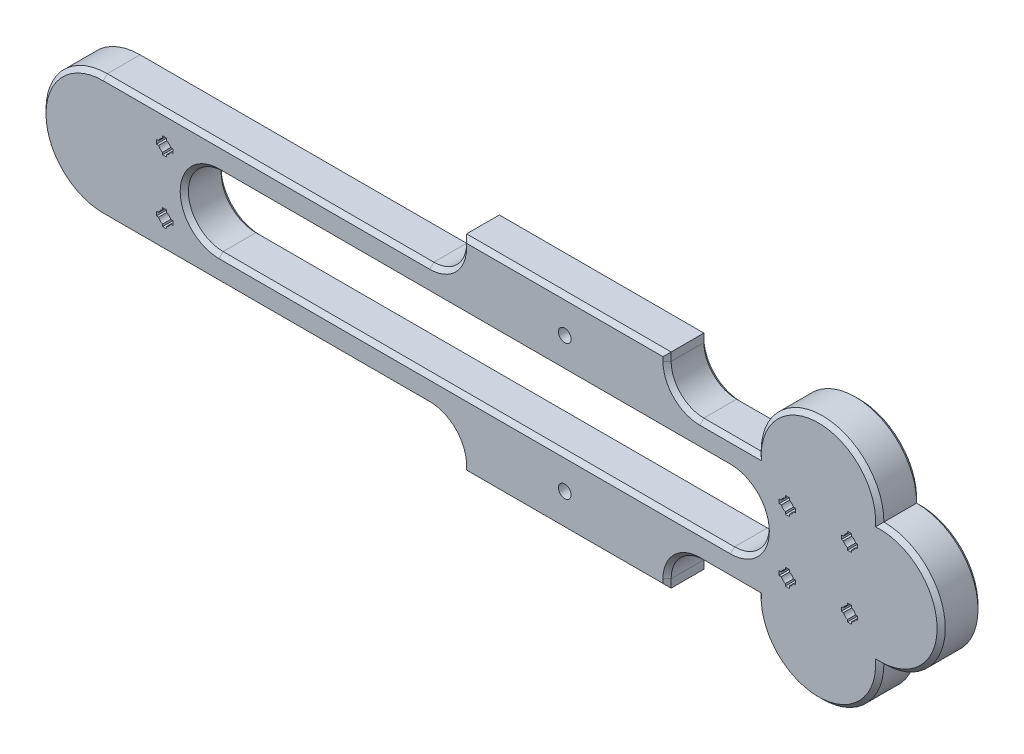
SolidWorks part; units mm, degrees
ref_plane "Front Plane" through (0, 0, 0) normal (0, 0, 1) x (1, 0, 0)
ref_plane "Top Plane" through (0, 0, 0) normal (0, 1, 0) x (1, 0, 0)
ref_plane "Right Plane" through (0, 0, 0) normal (1, 0, 0) x (0, 0, -1)
sketch "Sketch1" plane through (0, 0, 0) normal (0, 0, 1) x (1, 0, 0)
  line L0 (0, 0) -> (0, -33) construction
  line L1 (-25, -41.5) -> (25, -41.5)
  line L2 (-25, -41.5) -> (-25, 8.5)
  line L3 (-25, 8.5) -> (25, 8.5)
  line L4 (25, -41.5) -> (25, 8.5)
  line L5 (-25, -41.5) -> (25, 8.5) construction
  line L6 (-25, 8.5) -> (25, -41.5) construction
  line L7 (44.9072, -16.5) -> (118.6549, -16.5) construction
  line L8 (62, 0.7794) -> (62, -22.1936) construction
  line L9 (69.1, -10.9) -> (70.1, -10.9)
  line L10 (69.1, -10.9) -> (69.1, -10.3671)
  line L11 (69.1, -6.9) -> (70.1, -6.9)
  line L12 (70.1, -10.9) -> (70.1, -10.3671)
  line L13 (69.1, -10.9) -> (70.1, -6.9) construction
  line L14 (69.1, -6.9) -> (70.1, -10.9) construction
  line L15 (67.6, -9.4) -> (68.1329, -9.4)
  line L16 (67.6, -9.4) -> (67.6, -8.4)
  line L17 (67.6, -8.4) -> (68.1329, -8.4)
  line L18 (71.6, -9.4) -> (71.6, -8.4)
  line L19 (67.6, -9.4) -> (71.6, -8.4) construction
  line L20 (67.6, -8.4) -> (71.6, -9.4) construction
  line L21 (70.1, -7.4329) -> (70.1, -6.9)
  line L22 (71.0671, -8.4) -> (71.6, -8.4)
  line L23 (69.1, -7.4329) -> (69.1, -6.9)
  line L24 (71.0671, -9.4) -> (71.6, -9.4)
  line L25 (56.4, -9.4) -> (56.4, -8.4)
  line L26 (56.4, -8.4) -> (55.8671, -8.4)
  line L27 (54.9, -7.4329) -> (54.9, -6.9)
  line L28 (54.9, -6.9) -> (53.9, -6.9)
  line L29 (53.9, -7.4329) -> (53.9, -6.9)
  line L30 (52.9329, -8.4) -> (52.4, -8.4)
  line L31 (52.4, -9.4) -> (52.4, -8.4)
  line L32 (52.9329, -9.4) -> (52.4, -9.4)
  line L33 (53.9, -10.9) -> (53.9, -10.3671)
  line L34 (54.9, -10.9) -> (53.9, -10.9)
  line L35 (54.9, -10.9) -> (54.9, -10.3671)
  line L36 (56.4, -9.4) -> (55.8671, -9.4)
  line L37 (56.4, -23.6) -> (55.8671, -23.6)
  line L38 (54.9, -22.1) -> (54.9, -22.6329)
  line L39 (54.9, -22.1) -> (53.9, -22.1)
  line L40 (53.9, -22.1) -> (53.9, -22.6329)
  line L41 (52.9329, -23.6) -> (52.4, -23.6)
  line L42 (52.4, -23.6) -> (52.4, -24.6)
  line L43 (52.9329, -24.6) -> (52.4, -24.6)
  line L44 (53.9, -25.5671) -> (53.9, -26.1)
  line L45 (54.9, -26.1) -> (53.9, -26.1)
  line L46 (54.9, -25.5671) -> (54.9, -26.1)
  line L47 (56.4, -24.6) -> (55.8671, -24.6)
  line L48 (56.4, -23.6) -> (56.4, -24.6)
  line L49 (67.6, -23.6) -> (67.6, -24.6)
  line L50 (67.6, -24.6) -> (68.1329, -24.6)
  line L51 (69.1, -25.5671) -> (69.1, -26.1)
  line L52 (69.1, -26.1) -> (70.1, -26.1)
  line L53 (70.1, -25.5671) -> (70.1, -26.1)
  line L54 (71.0671, -24.6) -> (71.6, -24.6)
  line L55 (71.6, -23.6) -> (71.6, -24.6)
  line L56 (71.0671, -23.6) -> (71.6, -23.6)
  line L57 (70.1, -22.1) -> (70.1, -22.6329)
  line L58 (69.1, -22.1) -> (70.1, -22.1)
  line L59 (69.1, -22.1) -> (69.1, -22.6329)
  line L60 (67.6, -23.6) -> (68.1329, -23.6)
  line L61 (47, -31.5) -> (77, -31.5)
  line L62 (47, -31.5) -> (47, -1.5)
  line L63 (47, -1.5) -> (77, -1.5)
  line L64 (77, -31.5) -> (77, -1.5)
  line L65 (47, -31.5) -> (77, -1.5) construction
  line L66 (47, -1.5) -> (77, -31.5) construction
  line L67 (-98.3, -10.9) -> (-97.3, -10.9)
  line L68 (-98.3, -10.9) -> (-98.3, -10.3671)
  line L69 (-98.3, -6.9) -> (-97.3, -6.9)
  line L70 (-97.3, -10.9) -> (-97.3, -10.3671)
  line L71 (-99.8, -9.4) -> (-99.2671, -9.4)
  line L72 (-99.8, -9.4) -> (-99.8, -8.4)
  line L73 (-99.8, -8.4) -> (-99.2671, -8.4)
  line L74 (-95.8, -9.4) -> (-95.8, -8.4)
  line L75 (-97.3, -7.4329) -> (-97.3, -6.9)
  line L76 (-96.3329, -8.4) -> (-95.8, -8.4)
  line L77 (-98.3, -7.4329) -> (-98.3, -6.9)
  line L78 (-96.3329, -9.4) -> (-95.8, -9.4)
  line L79 (-99.8, -23.6) -> (-99.8, -24.6)
  line L80 (-99.8, -24.6) -> (-99.2671, -24.6)
  line L81 (-98.3, -25.5671) -> (-98.3, -26.1)
  line L82 (-98.3, -26.1) -> (-97.3, -26.1)
  line L83 (-97.3, -25.5671) -> (-97.3, -26.1)
  line L84 (-96.3329, -24.6) -> (-95.8, -24.6)
  line L85 (-95.8, -23.6) -> (-95.8, -24.6)
  line L86 (-96.3329, -23.6) -> (-95.8, -23.6)
  line L87 (-97.3, -22.1) -> (-97.3, -22.6329)
  line L88 (-98.3, -22.1) -> (-97.3, -22.1)
  line L89 (-98.3, -22.1) -> (-98.3, -22.6329)
  line L90 (-99.8, -23.6) -> (-99.2671, -23.6)
  line L91 (-97.8, -8.9) -> (-97.8, -24.1) construction
  line L92 (-82.8, -1.5) -> (-25, -1.5)
  line L93 (-112.8, -31.5) -> (-82.8, -31.5)
  line L94 (-112.8, -31.5) -> (-112.8, -1.5)
  line L95 (-112.8, -1.5) -> (-82.8, -1.5)
  line L96 (-82.8, -31.5) -> (-82.8, -1.5)
  line L97 (-112.8, -31.5) -> (-82.8, -1.5) construction
  line L98 (-112.8, -1.5) -> (-82.8, -31.5) construction
  line L99 (-82.8, -31.5) -> (-25, -31.5)
  line L100 (47, -1.5) -> (25, -1.5)
  line L101 (47, -31.5) -> (25, -31.5)
  circle A0 centre (0, 0) radius 1.55
  circle A1 centre (0, -33) radius 1.55
  arc A2 (69.1, -7.4329) -> (68.1329, -8.4) centre (69.6, -8.9) ccw
  arc A3 (68.1329, -9.4) -> (69.1, -10.3671) centre (69.6, -8.9) ccw
  arc A4 (71.0671, -8.4) -> (70.1, -7.4329) centre (69.6, -8.9) ccw
  arc A5 (70.1, -10.3671) -> (71.0671, -9.4) centre (69.6, -8.9) ccw
  arc A6 (54.9, -7.4329) -> (55.8671, -8.4) centre (54.4, -8.9) cw
  arc A7 (52.9329, -8.4) -> (53.9, -7.4329) centre (54.4, -8.9) cw
  arc A8 (53.9, -10.3671) -> (52.9329, -9.4) centre (54.4, -8.9) cw
  arc A9 (55.8671, -9.4) -> (54.9, -10.3671) centre (54.4, -8.9) cw
  arc A10 (55.8671, -23.6) -> (54.9, -22.6329) centre (54.4, -24.1) ccw
  arc A11 (53.9, -22.6329) -> (52.9329, -23.6) centre (54.4, -24.1) ccw
  arc A12 (52.9329, -24.6) -> (53.9, -25.5671) centre (54.4, -24.1) ccw
  arc A13 (54.9, -25.5671) -> (55.8671, -24.6) centre (54.4, -24.1) ccw
  arc A14 (69.1, -25.5671) -> (68.1329, -24.6) centre (69.6, -24.1) cw
  arc A15 (71.0671, -24.6) -> (70.1, -25.5671) centre (69.6, -24.1) cw
  arc A16 (70.1, -22.6329) -> (71.0671, -23.6) centre (69.6, -24.1) cw
  arc A17 (68.1329, -23.6) -> (69.1, -22.6329) centre (69.6, -24.1) cw
  arc A18 (47, -1.5) -> (77, -1.5) centre (62, -1.5) cw
  arc A19 (77, -1.5) -> (77, -31.5) centre (77, -16.5) cw
  arc A20 (77, -31.5) -> (47, -31.5) centre (62, -31.5) cw
  arc A21 (-98.3, -7.4329) -> (-99.2671, -8.4) centre (-97.8, -8.9) ccw
  arc A22 (-99.2671, -9.4) -> (-98.3, -10.3671) centre (-97.8, -8.9) ccw
  arc A23 (-96.3329, -8.4) -> (-97.3, -7.4329) centre (-97.8, -8.9) ccw
  arc A24 (-97.3, -10.3671) -> (-96.3329, -9.4) centre (-97.8, -8.9) ccw
  arc A25 (-98.3, -25.5671) -> (-99.2671, -24.6) centre (-97.8, -24.1) cw
  arc A26 (-96.3329, -24.6) -> (-97.3, -25.5671) centre (-97.8, -24.1) cw
  arc A27 (-97.3, -22.6329) -> (-96.3329, -23.6) centre (-97.8, -24.1) cw
  arc A28 (-99.2671, -23.6) -> (-98.3, -22.6329) centre (-97.8, -24.1) cw
  arc A29 (-112.8, -1.5) -> (-112.8, -31.5) centre (-112.8, -16.5) ccw
  point P5 (0, -16.5)
  point P10 (0, -16.5)
  point P83 (62, -16.5)
  point P90 (-97.8, -16.5)
  point P127 (44.9072, -16.5)
  point P128 (-97.8, -16.5)
  dimension "D1" = 3.1
  dimension "D2" = 33
  dimension "D3" = 50
  dimension "D4" = 50
  dimension "D5" = 30
  dimension "D6" = 30
  dimension "D7" = 152.2
  dimension "D8" = 62
  dimension "D9" = 7.6
  dimension "D10" = 15.2
  dimension "D11" = 7.6
  dimension "D12" = 15.2
extrude "Boss-Extrude1" add sketch "Sketch1" along normal blind 10 contours L94 A29 | L93 L96 L95 L94 A24 L70 L67 L68 A22 L71 L72 L73 A21 L77 L69 L75 A23 L76 L74 L78 L90 A28 L89 L88 L87 A27 L86 L85 L84 A26 L83 L82 L81 A25 L80 L79 | L96 L99 L2 L92 | L1 L4 L3 L2 A1 A0 | L101 L62 L100 L4 | L61 L64 L63 L62 A13 L46 L45 L44 A12 L43 L42 L41 A11 L40 L39 L38 A10 L37 L48 L47 A5 L12 L9 L10 A3 L15 L16 L17 A2 L23 L11 L21 A4 L22 L18 L24 L36 A9 L35 L34 L33 A8 L32 L31 L30 A7 L29 L28 | A18 L63 | A19 L64 | A20 L61
fillet "Fillet2" radius 8 4 edges at (25, -1.5, 5) (25, -31.5, 5) (-25, -31.5, 5) (-25, -1.5, 5)
chamfer "Chamfer1" distance 1 angle 45 36 edges at (-72.9, -1.5, 10) (-72.9, -1.5, 0) (-127.8, -16.5, 0) (-127.8, -16.5, 10) (-25, 7.5, 10) (-25, 7.5, 0) (0, 8.5, 0) (0, 8.5, 10) (25, 7.5, 10) (25, 7.5, 0) (40, -1.5, 0) (40, -1.5, 10) (62, 13.5, 0) (62, 13.5, 10) (92, -16.5, 0) (92, -16.5, 10) (62, -46.5, 0) (62, -46.5, 10) (40, -31.5, 10) (40, -31.5, 0) (25, -40.5, 0) (25, -40.5, 10) (0, -41.5, 0) (0, -41.5, 10) (-25, -40.5, 10) (-25, -40.5, 0) (-72.9, -31.5, 0) (-72.9, -31.5, 10) (27.3431, 0.8431, 10) (27.3431, 0.8431, 0) (27.3431, -33.8431, 10) (27.3431, -33.8431, 0) (-27.3431, 0.8431, 10) (-27.3431, 0.8431, 0) (-27.3431, -33.8431, 10) (-27.3431, -33.8431, 0)
sketch "Sketch2" plane through (0, 0, 0) normal (0, 0, -1) x (-1, 0, 0)
  circle A0 centre (0, 0) radius 3.25
  circle A1 centre (0, -33) radius 3.25
  dimension "D1" = 6.5
extrude "Cut-Extrude1" cut sketch "Sketch2" against normal blind 3
sketch "Sketch3" plane through (0, 0, 10) normal (0, 0, 1) x (1, 0, 0)
  line L0 (-84.5, -16.5) -> (40.5, -16.5) construction
  line L1 (-84.5, -8) -> (40.5, -8)
  line L2 (-84.5, -25) -> (40.5, -25)
  line L3 (-41.588, -2.5) -> (-41.588, -30.5) construction
  line L4 (-33, -2.5) -> (-112.8, -2.5) construction
  line L5 (-112.8, -30.5) -> (-33, -30.5) construction
  arc A0 (-84.5, -8) -> (-84.5, -25) centre (-84.5, -16.5) ccw
  arc A1 (40.5, -25) -> (40.5, -8) centre (40.5, -16.5) ccw
  circle A2 centre (0, 0) radius 1.55 construction
  point P2 (-22, -16.5)
  point P13 (-41.588, -16.5)
  point P14 (-21.2055, -16.5)
  dimension "D1" = 17
  dimension "D2" = 125
  dimension "D3" = 22
extrude "Cut-Extrude2" cut sketch "Sketch3" against normal through all
chamfer "Chamfer2" distance 1 angle 45 8 edges at (-22, -8, 10) (-22, -8, 0) (-93, -16.5, 10) (-93, -16.5, 0) (49, -16.5, 10) (49, -16.5, 0) (-22, -25, 10) (-22, -25, 0)
